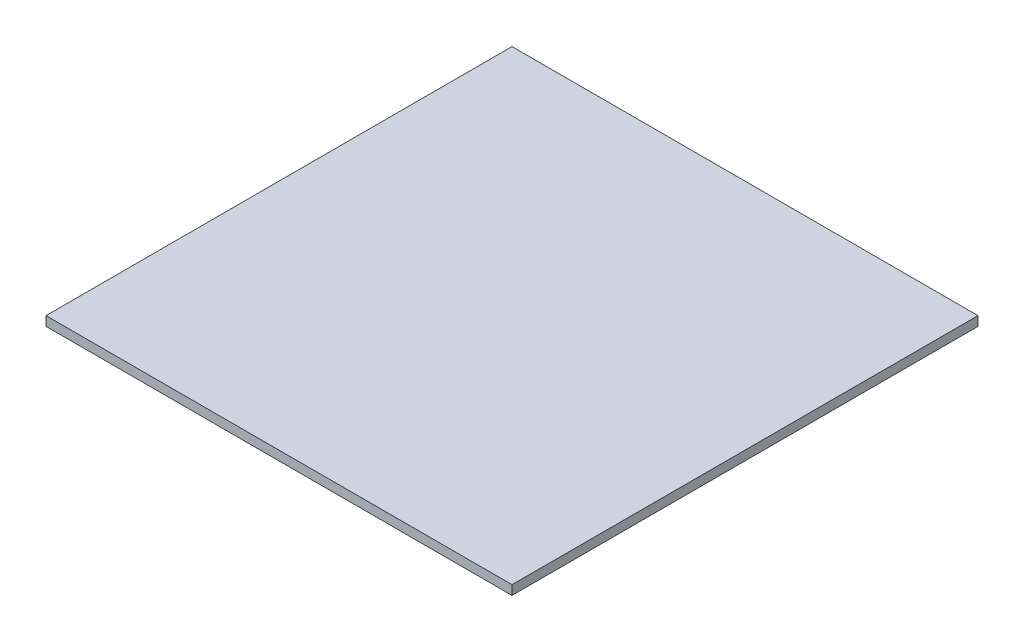
SolidWorks part; units mm, degrees
ref_plane "Front Plane" through (0, 0, 0) normal (0, 0, 1) x (1, 0, 0)
ref_plane "Top Plane" through (0, 0, 0) normal (0, 1, 0) x (1, 0, 0)
ref_plane "Right Plane" through (0, 0, 0) normal (1, 0, 0) x (0, 0, -1)
sketch "Sketch1" plane through (0, 0, 0) normal (0, 1, 0) x (1, 0, 0)
  line L1 (-250, -250) -> (250, -250)
  line L2 (-250, -250) -> (-250, 250)
  line L3 (-250, 250) -> (250, 250)
  line L4 (250, -250) -> (250, 250)
  line L5 (-250, -250) -> (250, 250) construction
  line L6 (-250, 250) -> (250, -250) construction
  point P0 (0, 0)
  dimension "D1" = 500
extrude "Boss-Extrude1" add sketch "Sketch1" along normal blind 10
